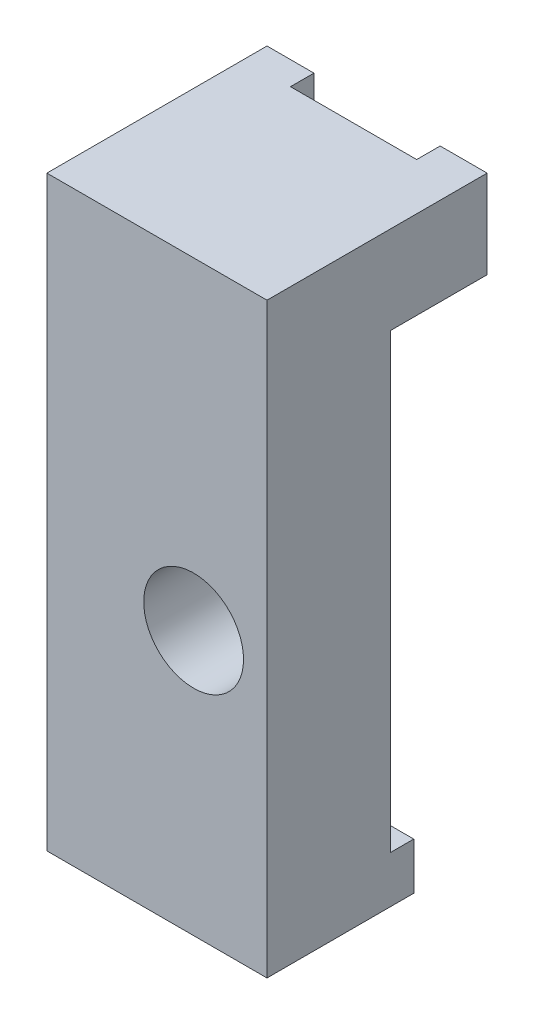
SolidWorks part; units mm, degrees
ref_plane "Front Plane" through (0, 0, 0) normal (0, 0, 1) x (1, 0, 0)
ref_plane "Top Plane" through (0, 0, 0) normal (0, 1, 0) x (1, 0, 0)
ref_plane "Right Plane" through (0, 0, 0) normal (1, 0, 0) x (0, 0, -1)
sketch "Sketch1" plane through (0, 0, 0) normal (0, 0, 1) x (1, 0, 0)
  line L1 (-4.7625, 12.7) -> (4.7625, 12.7)
  line L2 (-4.7625, 12.7) -> (-4.7625, -12.7)
  line L3 (-4.7625, -12.7) -> (4.7625, -12.7)
  line L4 (4.7625, 12.7) -> (4.7625, -12.7)
  line L5 (-4.7625, 12.7) -> (4.7625, -12.7) construction
  line L6 (-4.7625, -12.7) -> (4.7625, 12.7) construction
  point P0 (0, 0)
  dimension "D1" = 25.4
  dimension "D2" = 9.525
extrude "Boss-Extrude1" add sketch "Sketch1" along normal mid plane 9.525
sketch "Sketch2" plane through (4.7625, 0, 0) normal (1, 0, 0) x (0, 0, -1)
  line L0 (-4.7625, -12.7) -> (-4.7625, 12.7) construction
  line L1 (4.7625, -12.7) -> (1.5875, -12.7)
  line L2 (4.7625, -12.7) -> (4.7625, 8.89)
  line L3 (4.7625, 8.89) -> (1.5875, 8.89)
  line L4 (1.5875, -12.7) -> (1.5875, 8.89)
  line L5 (-4.7625, 12.7) -> (4.7625, 12.7) construction
  dimension "D1" = 6.35
  dimension "D2" = 3.81
extrude "Cut-Extrude1" cut sketch "Sketch2" against normal up to next
sketch "Sketch3" plane through (0, 0, 4.7625) normal (0, 0, 1) x (1, 0, 0)
  line L0 (-4.7625, -12.7) -> (4.7625, -12.7) construction
  line L2 (4.7625, -12.7) -> (4.7625, 12.7) construction
  circle A0 centre (1.5875, -1.27) radius 2.159
  dimension "D1" = 11.43
  dimension "D2" = 3.175
extrude "Cut-Extrude2" cut sketch "Sketch3" against normal up to next
sketch "Sketch4" plane through (0, 12.7, 0) normal (0, 1, 0) x (1, 0, 0)
  line L0 (4.7625, 4.7625) -> (-4.7625, 4.7625) construction
  line L1 (2.7305, 4.7625) -> (-2.7305, 4.7625)
  line L2 (2.7305, 4.7625) -> (2.7305, 3.7465)
  line L3 (2.7305, 3.7465) -> (-2.7305, 3.7465)
  line L4 (-2.7305, 4.7625) -> (-2.7305, 3.7465)
  line L5 (-4.7625, -4.7625) -> (-4.7625, 4.7625) construction
  line L6 (4.7625, -4.7625) -> (4.7625, 4.7625) construction
  dimension "D1" = 2.032
  dimension "D2" = 2.032
  dimension "D3" = 1.016
extrude "Cut-Extrude3" cut sketch "Sketch4" against normal up to next
sketch "Sketch5" plane through (4.7625, 0, 0) normal (1, 0, 0) x (0, 0, -1)
  line L0 (1.5875, 8.89) -> (1.5875, -12.7) construction
  line L1 (1.5875, -10.668) -> (0.5715, -10.668)
  line L2 (1.5875, -10.668) -> (1.5875, 8.89)
  line L3 (1.5875, 8.89) -> (0.5715, 8.89)
  line L4 (0.5715, -10.668) -> (0.5715, 8.89)
  line L5 (-4.7625, -12.7) -> (1.5875, -12.7) construction
  line L6 (4.7625, 8.89) -> (1.5875, 8.89) construction
  dimension "D1" = 2.032
  dimension "D2" = 1.016
extrude "Cut-Extrude4" cut sketch "Sketch5" against normal through all
